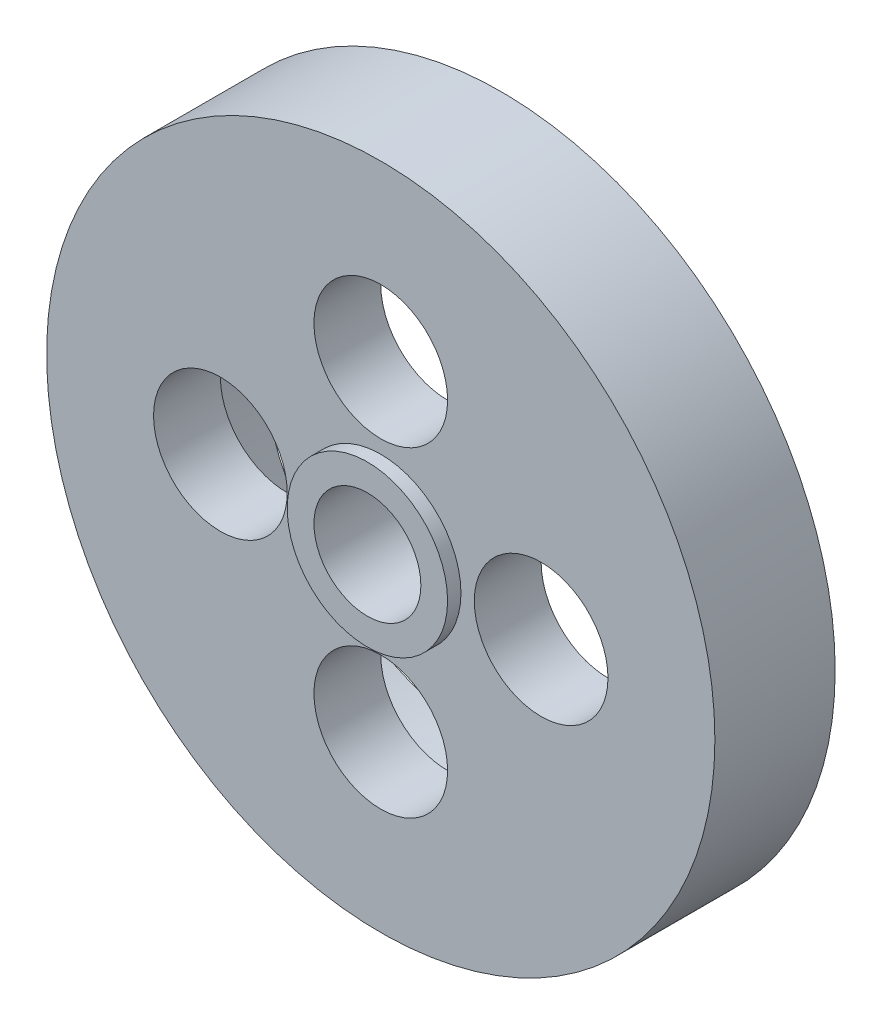
SolidWorks part; units mm, degrees
material "Gray Cast Iron"
ref_plane "Front Plane" through (0, 0, 0) normal (0, 0, 1) x (1, 0, 0)
ref_plane "Top Plane" through (0, 0, 0) normal (0, 1, 0) x (1, 0, 0)
ref_plane "Right Plane" through (0, 0, 0) normal (1, 0, 0) x (0, 0, -1)
sketch "Sketch2" plane through (0, 0, 0) normal (0, 0, 1) x (1, 0, 0)
  circle A0 centre (0, 0) radius 25
  circle A1 centre (0, 0) radius 12 construction
  circle A2 centre (0, 12) radius 5
  circle A3 centre (12, 0) radius 5
  circle A4 centre (0, -12) radius 5
  circle A5 centre (-12, 0) radius 5
  circle A6 centre (0, 0) radius 4
  dimension "D1" = 50
  dimension "D2" = 24
  dimension "D3" = 10
  dimension "D4" = 8
extrude "Boss-Extrude1" add sketch "Sketch2" along normal blind 9
sketch "Sketch3" plane through (0, 0, 0) normal (0, 0, -1) x (-1, 0, 0)
  circle A0 centre (0, 0) radius 18
  dimension "D1" = 36
extrude "Cut-Extrude1" cut sketch "Sketch3" against normal blind 4
sketch "Sketch4" plane through (0, 0, 9) normal (0, 0, 1) x (1, 0, 0)
  circle A0 centre (0, 0) radius 6
  circle A1 centre (0, 0) radius 4 construction
  circle A2 centre (0, 0) radius 4
  dimension "D1" = 12
extrude "Boss-Extrude2" add sketch "Sketch4" along normal blind 1
